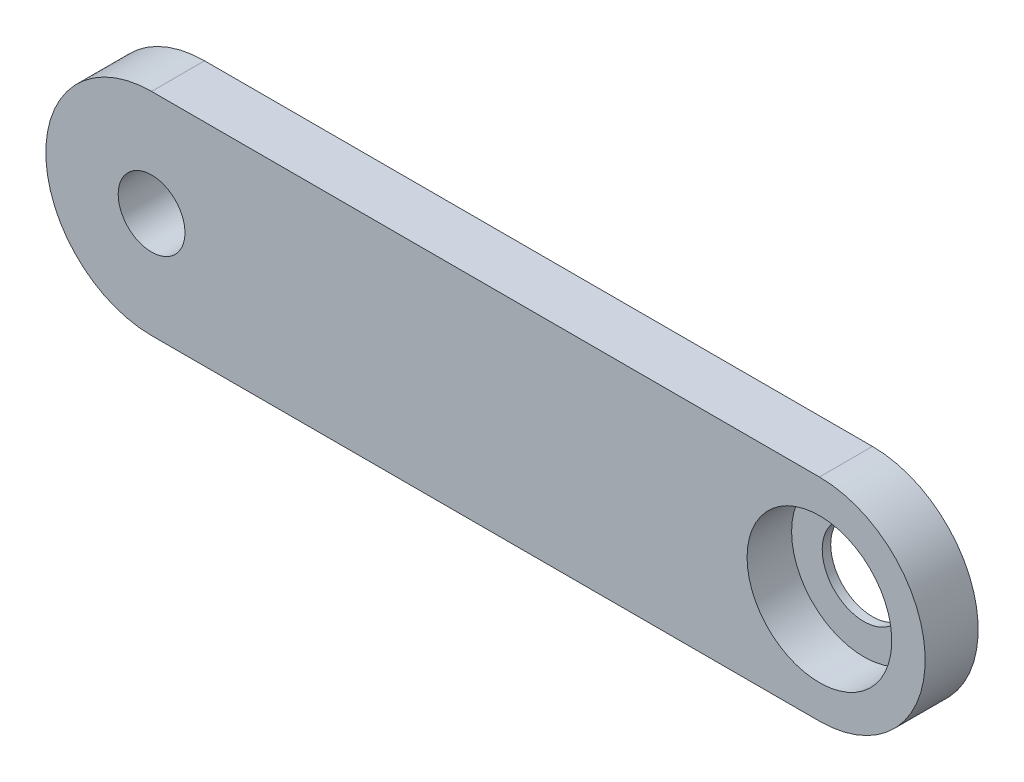
SolidWorks part; units mm, degrees
ref_plane "Alzado" through (0, 0, 0) normal (0, 0, 1) x (1, 0, 0)
ref_plane "Planta" through (0, 0, 0) normal (0, 1, 0) x (1, 0, 0)
ref_plane "Vista lateral" through (0, 0, 0) normal (1, 0, 0) x (0, 0, -1)
sketch "Croquis1" plane through (0, 0, 0) normal (0, 0, 1) x (1, 0, 0)
  line L0 (0, 0) -> (120, 0) construction
  line L1 (0, 19) -> (120, 19)
  line L2 (0, -19) -> (120, -19)
  arc A0 (0, 19) -> (0, -19) centre (0, 0) ccw
  arc A1 (120, -19) -> (120, 19) centre (120, 0) ccw
  circle A2 centre (0, 0) radius 6
  circle A3 centre (120, 0) radius 13
  point P3 (60, 0)
  dimension "D3" = 12
  dimension "D4" = 26
  dimension "D1" = 120
  dimension "D2" = 38
extrude "Saliente-Extruir1" add sketch "Croquis1" along normal blind 9.525
sketch "Croquis2" plane through (0, 0, 0) normal (0, 0, -1) x (-1, 0, 0)
  circle A0 centre (-120, 0) radius 13 construction
  circle A1 centre (-120, 0) radius 13
  circle A2 centre (-120, 0) radius 7.5
  dimension "D1" = 15
extrude "Saliente-Extruir2" add sketch "Croquis2" against normal blind 1.525
